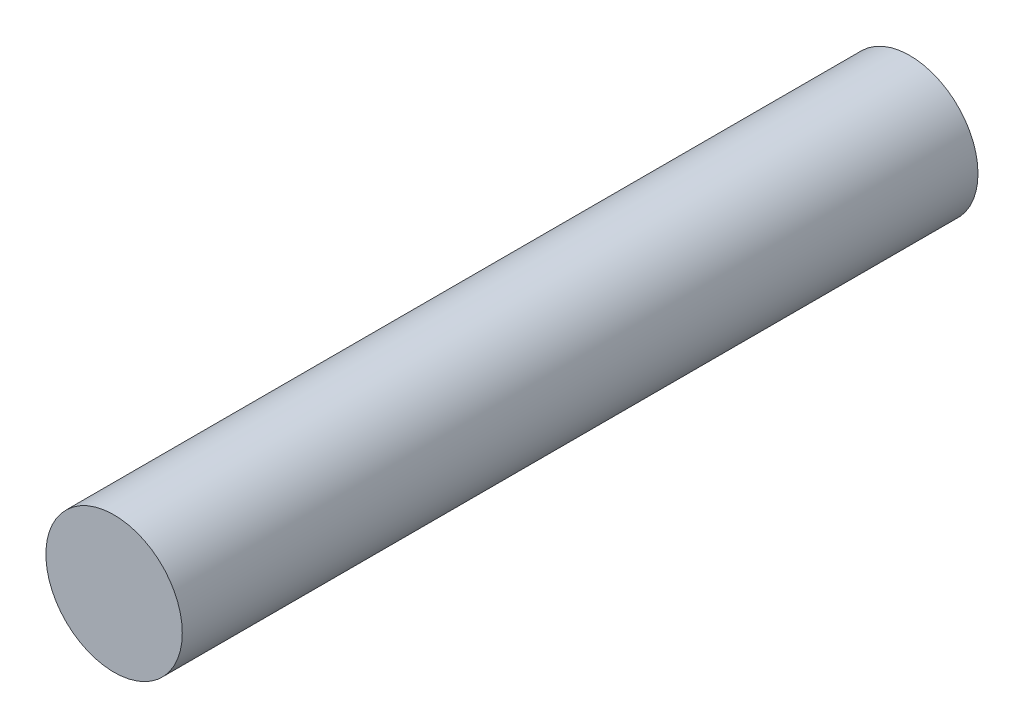
SolidWorks part; units mm, degrees
ref_plane "Front Plane" through (0, 0, 0) normal (0, 0, 1) x (1, 0, 0)
ref_plane "Top Plane" through (0, 0, 0) normal (0, 1, 0) x (1, 0, 0)
ref_plane "Right Plane" through (0, 0, 0) normal (1, 0, 0) x (0, 0, -1)
sketch "Sketch1" plane through (0, 0, 0) normal (0, 0, 1) x (1, 0, 0)
  circle A0 centre (0, 0) radius 30
  point P4 (0, 0)
  dimension "D1" = 60
extrude "Boss-Extrude1" add sketch "Sketch1" along normal blind 350
sketch "Sketch2" plane through (0, 0, 350) normal (0, 0, 1) x (1, 0, 0)
  point P0 (0, 0)
